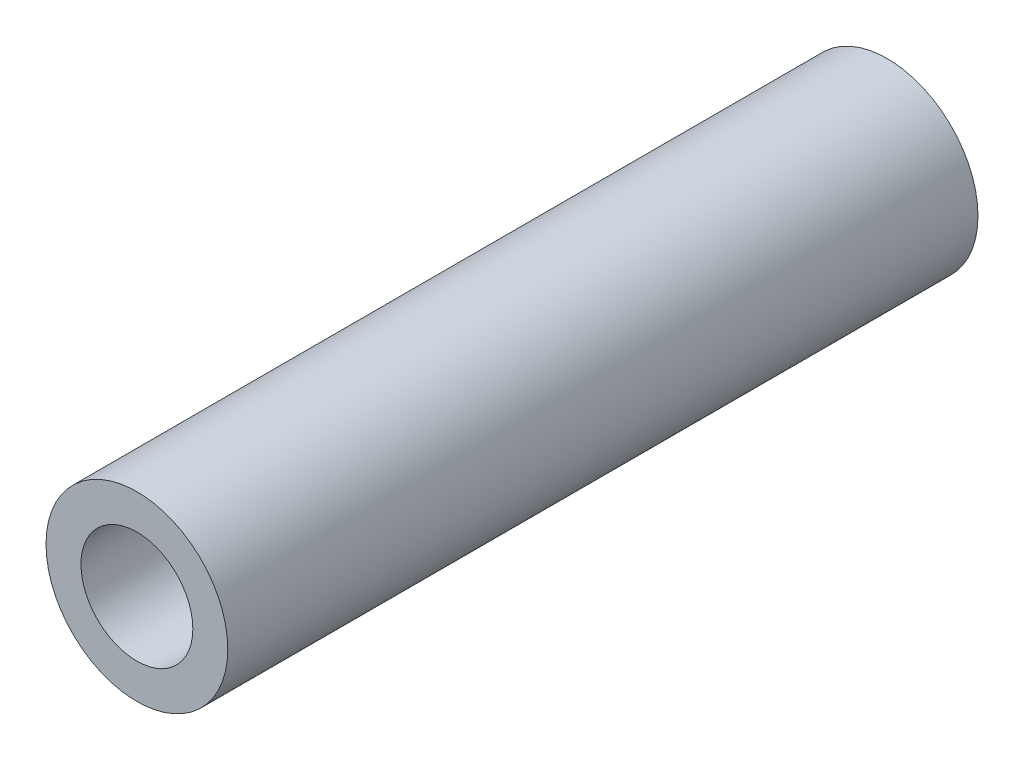
SolidWorks part; units mm, degrees
material "PLA"
ref_plane "Front Plane" through (0, 0, 0) normal (0, 0, 1) x (1, 0, 0)
ref_plane "Top Plane" through (0, 0, 0) normal (0, 1, 0) x (1, 0, 0)
ref_plane "Right Plane" through (0, 0, 0) normal (1, 0, 0) x (0, 0, -1)
sketch "Sketch1" plane through (0, 0, 0) normal (0, 0, 1) x (1, 0, 0)
  circle A1 centre (106.6535, 0) radius 4
  circle A2 centre (106.6535, 0) radius 6.5
  dimension "D2" = 13
  dimension "D1" = 8
extrude "Boss-Extrude1" add sketch "Sketch1" along normal up to surface (53.65 mm away)
